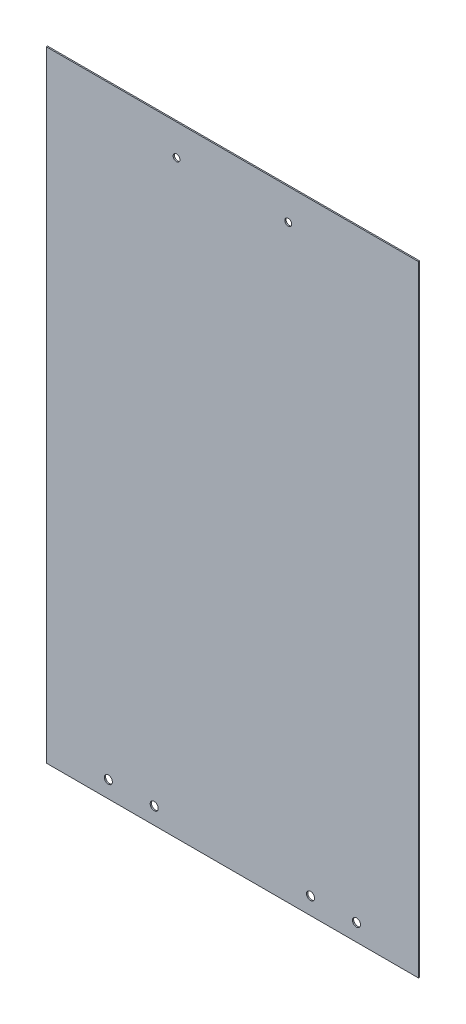
SolidWorks part; units mm, degrees
material "PE High Density"
ref_plane "Front Plane" through (0, 0, 0) normal (0, 0, 1) x (1, 0, 0)
ref_plane "Top Plane" through (0, 0, 0) normal (0, 1, 0) x (1, 0, 0)
ref_plane "Right Plane" through (0, 0, 0) normal (1, 0, 0) x (0, 0, -1)
ref_plane "Plane1" through (0, 0, -0.1) normal (0, 0, -1) x (-1, 0, 0)
sketch "Sketch1" plane through (0, 0, -0.1) normal (0, 0, -1) x (-1, 0, 0)
  line L0 (-325, 500) -> (-625, 500)
  line L1 (-625, 500) -> (-625, 0)
  line L2 (-625, 0) -> (-325, 0)
  line L3 (-325, 0) -> (-325, 500)
  dimension "D1" = 500
  dimension "D2" = 300
extrude "Boss-Extrude1" add sketch "Sketch1" against normal blind 1
sketch "Sketch2" plane through (0, 0, -0.1) normal (0, 0, -1) x (-1, 0, 0)
  line L1 (-625, 500) -> (-625, 0) construction
  circle A0 centre (-538, 13.75) radius 3.25
  circle A1 centre (-575, 13.75) radius 3.25
  dimension "D1" = 37
  dimension "D2" = 50
extrude "Cut-Extrude1" cut sketch "Sketch2" against normal through all
sketch "Sketch3" plane through (0, 0, -0.1) normal (0, 0, -1) x (-1, 0, 0)
  line L0 (-475, 500) -> (-475, 279.1708) construction
  line L2 (-625, 0) -> (-325, 0) construction
  circle A0 centre (-520, 475) radius 2.75
  circle A1 centre (-430, 475) radius 2.75
  dimension "D2" = 5.5
  dimension "D3" = 5.5
  dimension "D1" = 90
  dimension "D4" = 475
extrude "M5 clearance- 5.5 mm -thru" cut sketch "Sketch3" against normal through all
hole_wizard "Ø6.5 (6.5) Diameter Slot2" positions "Sketch7" profile "Sketch8" size "Ø6.5" standard "ANSI Metric" slot yes end condition through all
sketch "Sketch7" plane through (0, 0, -0.1) normal (0, 0, -1) x (-1, 0, 0)
  line L0 (-325, 0) -> (-325, 500) construction
  line L1 (-625, 0) -> (-325, 0) construction
  point P0 (-412, 13.5)
  point P2 (-375, 13.5)
  dimension "D3" = 13.5
  dimension "D1" = 37
  dimension "D2" = 50
  dimension "D4" = 13.5
sketch "Sketch8" plane through (412, 13.5, -0.1) normal (1, 0, 0) x (0, 1, 0)
  line L0 (0, 0) -> (0, 1)
  line L1 (0, 1) -> (3.25, 1)
  line L2 (3.25, 1) -> (3.25, 0)
  line L5 (3.25, 0) -> (0, 0)
  line L11 (0, -6.35) -> (0, 107.95) construction
  dimension "Thru Hole Dia." = 6.5
  dimension "Thru Hole Depth" = 1
